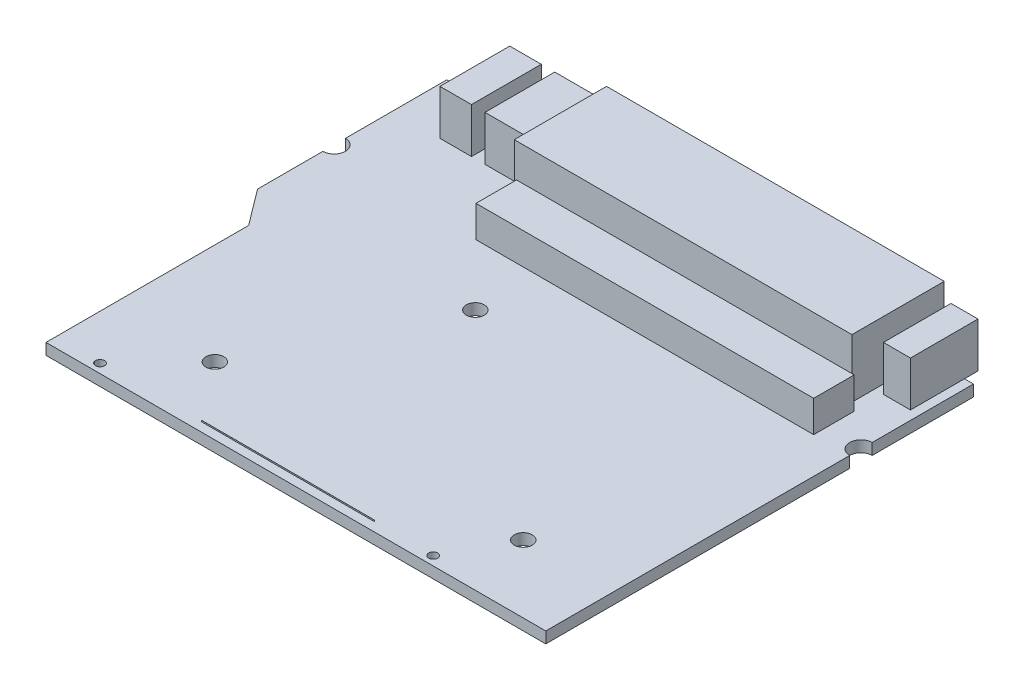
SolidWorks part; units mm, degrees
ref_plane "Front Plane" through (0, 0, 0) normal (0, 0, 1) x (1, 0, 0)
ref_plane "Top Plane" through (0, 0, 0) normal (0, 1, 0) x (1, 0, 0)
ref_plane "Right Plane" through (0, 0, 0) normal (1, 0, 0) x (0, 0, -1)
sketch "Sketch1" plane through (0, 0, 0) normal (0, 1, 0) x (1, 0, 0)
  line L0 (58.5, -47.5) -> (-52.5, -47.5) construction
  line L1 (-58.5, 47.5) -> (58.5, 47.5)
  line L2 (-58.5, 47.5) -> (-58.5, 25)
  line L3 (-52.5, -47.5) -> (58.5, -47.5)
  line L4 (58.5, 47.5) -> (58.5, 25)
  line L5 (-58.5, 47.5) -> (58.5, -47.5) construction
  line L6 (-58.5, -47.5) -> (58.5, 47.5) construction
  line L7 (-58.5, -47.5) -> (-58.5, -2.5) construction
  line L8 (-58.5, 47.5) -> (-58.5, 5.5) construction
  line L9 (-52.5, -47.5) -> (-52.5, -2.5)
  line L10 (-52.5, -2.5) -> (-58.5, 5.5)
  line L11 (58.5, -47.5) -> (58.5, 22.5) construction
  line L12 (58.5, 22.5) -> (56, 22.5) construction
  line L13 (58.5, 20) -> (58.5, -47.5)
  line L14 (-58.5, 22.5) -> (-56, 22.5) construction
  line L15 (-58.5, 20) -> (-58.5, 5.5)
  arc A0 (58.5, 25) -> (58.5, 20) centre (58.5, 22.5) ccw
  arc A1 (-58.5, 20) -> (-58.5, 25) centre (-58.5, 22.5) ccw
  point P0 (0, 0)
  dimension "D1" = 117
  dimension "D2" = 95
  dimension "D3" = 111
  dimension "D4" = 45
  dimension "D5" = 42
  dimension "D6" = 70
  dimension "D7" = 2.5
  dimension "D8" = 2.5
extrude "Boss-Extrude1" add sketch "Sketch1" along normal blind 2.5
sketch "Sketch2" plane through (0, 2.5, 0) normal (0, 1, 0) x (1, 0, 0)
  line L0 (-52.5, -47.5) -> (-11.0541, 6.4095) construction
  line L1 (-11.0541, 6.4095) -> (58.5, -47.5) construction
  line L2 (-52.5, -32.5) -> (58.5, -32.5) construction
  line L3 (-52.5, -2.5) -> (-52.5, -47.5) construction
  line L4 (58.5, -47.5) -> (58.5, 20) construction
  line L5 (-52.5, -47.5) -> (58.5, -47.5) construction
  line L6 (-52.5, -47.5) -> (-42.5, -47.5) construction
  line L7 (58.5, -47.5) -> (31.5, -47.5) construction
  line L8 (-42.5, -47.5) -> (-42.5, -45.5) construction
  line L9 (31.5, -47.5) -> (31.5, -45.5) construction
  circle A0 centre (-11.0541, 6.4095) radius 2
  circle A1 centre (-30, -32.5) radius 2
  circle A2 centre (38.5, -32.5) radius 2
  circle A3 centre (-42.5, -45.5) radius 1
  circle A4 centre (31.5, -45.5) radius 1
  dimension "D3" = 4
  dimension "D5" = 4
  dimension "D6" = 4
  dimension "D1" = 68
  dimension "D2" = 88
  dimension "D4" = 15
  dimension "D7" = 22.5
  dimension "D8" = 20
  dimension "D9" = 10
  dimension "D10" = 27
  dimension "D11" = 2
  dimension "D12" = 2
extrude "Cut-Extrude1" cut sketch "Sketch2" against normal blind 5
sketch "Sketch3" plane through (0, 2.5, 0) normal (0, 1, 0) x (1, 0, 0)
  line L1 (58.5, 47.5) -> (-58.5, 47.5) construction
  line L2 (-26.5, 47.5) -> (-26.5, 30.5)
  line L3 (-26.5, 30.5) -> (48.5, 30.5)
  line L4 (48.5, 30.5) -> (48.5, 47.5)
  line L5 (48.5, 47.5) -> (48.5, 51)
  line L6 (48.5, 51) -> (-26.5, 51)
  line L7 (-26.5, 51) -> (-26.5, 47.5)
  dimension "D1" = 32
  dimension "D2" = 10
  dimension "D3" = 75
  dimension "D4" = 3.5
  dimension "D5" = 17
extrude "Boss-Extrude2" add sketch "Sketch3" along normal blind 13
sketch "Sketch6" plane through (0, 2.5, 0) normal (0, 1, 0) x (1, 0, 0)
  line L0 (58.5, 25) -> (58.5, 47.5) construction
  line L1 (-24.5, 20) -> (50.5, 20)
  line L2 (-24.5, 20) -> (-24.5, 29)
  line L3 (-24.5, 29) -> (50.5, 29)
  line L4 (50.5, 20) -> (50.5, 29)
  line L5 (-26.5, 30.5) -> (48.5, 30.5) construction
  dimension "D1" = 75
  dimension "D2" = 8
  dimension "D3" = 9
  dimension "D4" = 1.5
extrude "Boss-Extrude3" add sketch "Sketch6" along normal blind 7
sketch "Sketch7" plane through (0, 2.5, 0) normal (0, 1, 0) x (1, 0, 0)
  line L3 (50.5, 47.5) -> (50.5, 35.5)
  line L4 (50.5, 35.5) -> (56.5, 35.5)
  line L5 (56.5, 35.5) -> (56.5, 47.5)
  line L6 (-29.5, 47.5) -> (-29.5, 35.5)
  line L7 (-29.5, 35.5) -> (-38, 35.5)
  line L9 (-26.5, 47.5) -> (-58.5, 47.5) construction
  line L10 (-38, 35.5) -> (-38, 47.5)
  line L11 (-41, 35.5) -> (-48, 35.5)
  line L12 (-48, 35.5) -> (-48, 47.5)
  line L13 (-41, 35.5) -> (-41, 47.5)
  line L14 (-29.5, 47.5) -> (-29.5, 51)
  line L15 (-29.5, 51) -> (-38, 51)
  line L16 (-38, 51) -> (-38, 47.5)
  line L17 (-41, 47.5) -> (-41, 51)
  line L18 (-41, 51) -> (-48, 51)
  line L19 (-48, 51) -> (-48, 47.5)
  line L20 (56.5, 47.5) -> (56.5, 50.5)
  line L21 (56.5, 50.5) -> (50.5, 50.5)
  line L22 (50.5, 50.5) -> (50.5, 47.5)
  dimension "D1" = 6
  dimension "D2" = 12
  dimension "D3" = 3
  dimension "D4" = 10.5
  dimension "D5" = 3
  dimension "D6" = 8.5
  dimension "D7" = 7
  dimension "D8" = 12
  dimension "D9" = 3.5
  dimension "D10" = 3
extrude "Boss-Extrude4" add sketch "Sketch7" along normal blind 10
sketch "Sketch8" plane through (0, 2.5, 0) normal (0, 1, 0) x (1, 0, 0)
  line L0 (58.5, -47.5) -> (18.5, -47.5) construction
  line L1 (-52.5, -47.5) -> (58.5, -47.5) construction
  line L2 (-52.5, -47.5) -> (-20, -47.5) construction
  line L3 (-20, -47.5) -> (-20, -45.5) construction
  line L4 (-20, -45.5) -> (18.5, -45.5)
  line L5 (18.5, -45.5) -> (18.5, -45.49)
  line L6 (18.5, -45.49) -> (-20, -45.49)
  line L7 (-20, -45.49) -> (-20, -45.5)
  dimension "D1" = 32.5
  dimension "D2" = 40
  dimension "D3" = 2
  dimension "D4" = 0.01
extrude "Boss-Extrude5" add sketch "Sketch8" along normal blind 0.3
